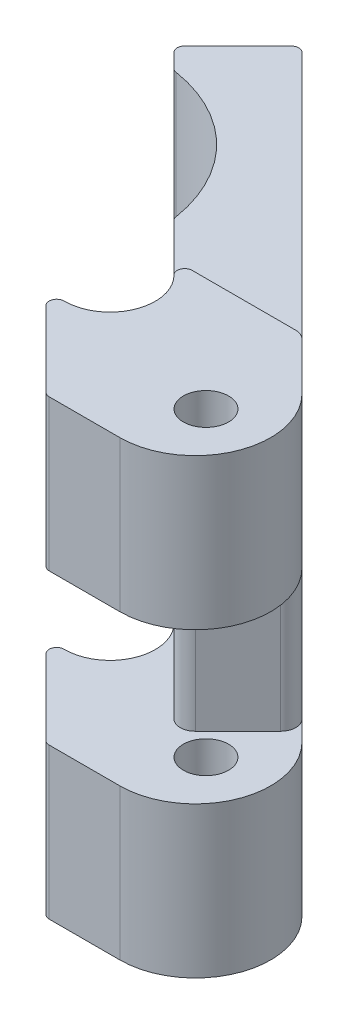
SolidWorks part; units mm, degrees
ref_plane "前视基准面" through (0, 0, 0) normal (0, 0, 1) x (1, 0, 0)
ref_plane "上视基准面" through (0, 0, 0) normal (0, 1, 0) x (1, 0, 0)
ref_plane "右视基准面" through (0, 0, 0) normal (1, 0, 0) x (0, 0, -1)
sketch "Sketch1" plane through (0, 0, 0) normal (0, 1, 0) x (1, 0, 0)
  line L0 (0, 0) -> (23.163, -23.163)
  line L1 (21.0416, -28.2843) -> (0, -28.2843)
  line L2 (0, 3.0516) -> (0, -30.2047) construction
  line L3 (4.2426, 4.2426) -> (34.234, -25.7487)
  line L4 (30.6985, -34.2843) -> (0, -34.2843)
  line L5 (0, 0) -> (4.2426, 4.2426)
  line L6 (0, -28.2843) -> (0, -34.2843)
  line L7 (4.2426, 4.2426) -> (42.7696, -34.2843) construction
  line L8 (42.7696, -34.2843) -> (0, -34.2843) construction
  line L9 (0, 0) -> (28.2843, -28.2843) construction
  line L10 (28.2843, -28.2843) -> (0, -28.2843) construction
  line L11 (21.0416, -25.2843) -> (30.6985, -29.2843) construction
  line L12 (30.6985, -29.2843) -> (46.0994, -35.6635) construction
  arc A0 (34.234, -25.7487) -> (30.6985, -34.2843) centre (30.6985, -29.2843) cw
  arc A1 (23.163, -23.163) -> (21.0416, -28.2843) centre (21.0416, -25.2843) cw
  circle A2 centre (31.9056, -29.7843) radius 1.6
  point P15 (28.2843, -28.2843)
  dimension "D4" = 5
  dimension "D5" = 3
  dimension "D6" = 3.2
  dimension "D1" = 40
  dimension "D2" = 45
  dimension "D7" = 4.5
  dimension "D3" = 6
extrude "Boss-Extrude1" add sketch "Sketch1" along normal blind 10
sketch "Sketch2" plane through (0, 10, 0) normal (0, 1, 0) x (1, 0, 0)
  line L1 (1.4142, -1.4142) -> (9.8995, -9.8995)
  line L2 (4.2426, 4.2426) -> (0, 0) construction
  line L3 (0, 0) -> (23.163, -23.163) construction
  line L5 (0, -28.2843) -> (0, -34.2843)
  line L11 (19.799, -28.2843) -> (25.799, -34.2843)
  line L12 (0, -28.2843) -> (19.799, -28.2843)
  line L13 (21.0416, -28.2843) -> (0, -28.2843) construction
  line L14 (0, -34.2843) -> (25.799, -34.2843)
  line L15 (0, -34.2843) -> (30.6985, -34.2843) construction
  line L16 (34.234, -25.7487) -> (4.2426, 4.2426) construction
  arc A1 (9.8995, -9.8995) -> (1.4142, -1.4142) centre (0, -11.3137) ccw
  dimension "D1" = 8
  dimension "D4" = 10
  dimension "D2" = 12
  dimension "D3" = 8
extrude "Cut-Extrude1" cut sketch "Sketch2" against normal through all
fillet "Fillet1" radius 0.5 6 edges at (25.799, 5, 34.2843) (19.799, 5, 28.2843) (1.4142, 5, 1.4142) (9.8995, 5, 9.8995) (0, 5, 0) (4.2426, 5, -4.2426)
sketch "Sketch3" plane through (0, 10, 0) normal (0, 1, 0) x (1, 0, 0)
  line L0 (20.6525, -29.1378) -> (25.6525, -34.1378)
  line L1 (26.0061, -34.2843) -> (30.6985, -34.2843)
  line L2 (22.2843, -22.2843) -> (30.3553, -22.2843)
  line L3 (31.0624, -22.5772) -> (34.234, -25.7487)
  line L4 (34.234, -25.7487) -> (4.5962, 3.8891) construction
  line L5 (22.2843, -22.2843) -> (23.163, -23.163)
  line L6 (10.0158, -10.0158) -> (23.163, -23.163) construction
  line L7 (21.0061, -28.2843) -> (21.0416, -28.2843)
  circle A2 centre (31.9056, -29.7843) radius 1.5
  arc A3 (21.0061, -28.2843) -> (20.6525, -29.1378) centre (21.0061, -28.7843) ccw
  arc A4 (25.6525, -34.1378) -> (26.0061, -34.2843) centre (26.0061, -33.7843) ccw
  arc A6 (30.3553, -22.2843) -> (31.0624, -22.5772) centre (30.3553, -23.2843) cw
  arc A7 (23.163, -23.163) -> (21.0416, -28.2843) centre (21.0416, -25.2843) cw
  arc A8 (21.0416, -28.2843) -> (23.163, -23.163) centre (21.0416, -25.2843) ccw construction
  arc A9 (30.6985, -34.2843) -> (34.234, -25.7487) centre (30.6985, -29.2843) ccw
  arc A10 (30.6985, -34.2843) -> (34.234, -25.7487) centre (30.6985, -29.2843) ccw construction
  dimension "D1" = 3
  dimension "D2" = 1.2426
  dimension "D3" = 1
  dimension "D4" = 1
  dimension "D5" = 1
extrude "Boss-Extrude2" add sketch "Sketch3" along normal blind 10 and the other way blind 20
sketch "Sketch4" plane through (0, 0, 0) normal (-0.7071, 0, 0.7071) x (0.7071, 0, 0.7071)
  line L0 (31.5147, 10) -> (41.5147, 10)
  line L1 (41.5147, 10) -> (41.5147, 0)
  line L2 (41.5147, 0) -> (31.5147, 0)
  line L3 (31.5147, 0) -> (31.5147, 10)
  dimension "D1" = 10
extrude "Cut-Extrude3" cut sketch "Sketch4" along normal through all
sketch "Sketch5" plane through (-4.2426, 0, 4.2426) normal (-0.7071, 0, 0.7071) x (0.7071, 0, 0.7071)
  line L4 (41.5147, 10) -> (50.1784, 10)
  line L5 (50.1784, 10) -> (50.1784, 0)
  line L6 (50.1784, 0) -> (41.5147, 0)
  line L7 (41.5147, 0) -> (41.5147, 10)
extrude "Cut-Extrude5" cut sketch "Sketch5" against normal through all
fillet "Fillet3" radius 0.5 2 edges at (22.2843, 15, 22.2843) (22.2843, -5, 22.2843)
fillet "Fillet4" radius 1 2 edges at (33.598, 5, 25.1127) (29.3553, 5, 29.3553)
